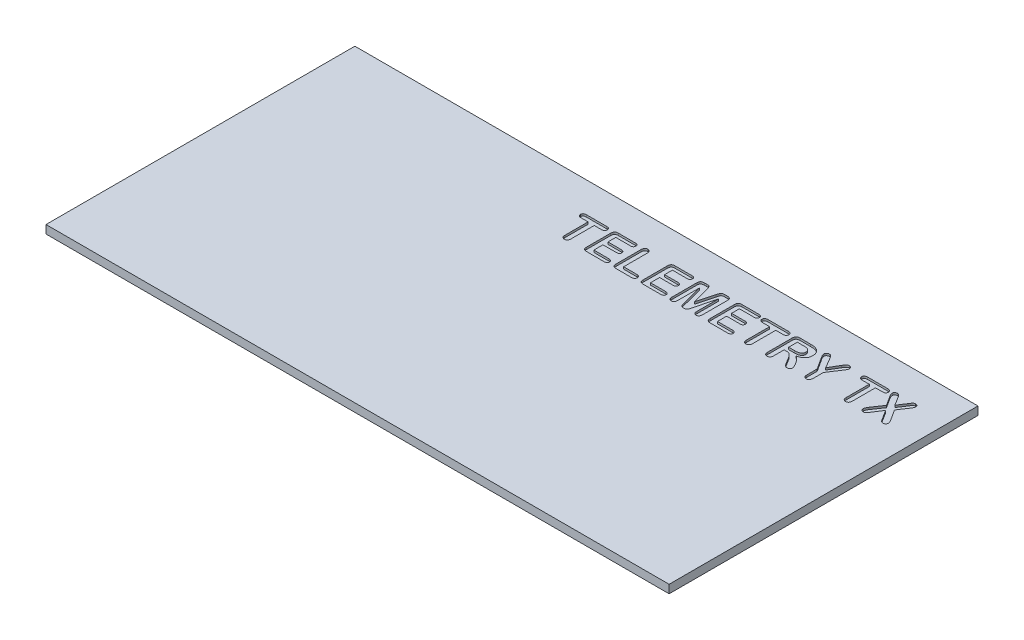
SolidWorks part; units mm, degrees
ref_plane "Front Plane" through (0, 0, 0) normal (0, 0, 1) x (1, 0, 0)
ref_plane "Top Plane" through (0, 0, 0) normal (0, 1, 0) x (1, 0, 0)
ref_plane "Right Plane" through (0, 0, 0) normal (1, 0, 0) x (0, 0, -1)
sketch "Sketch1" plane through (0, 0, 0) normal (0, 1, 0) x (1, 0, 0)
  line L5 (-75.35, 37.35) -> (75.35, 37.35)
  line L6 (-75.35, 37.35) -> (-75.35, -37.35)
  line L7 (-75.35, -37.35) -> (75.35, -37.35)
  line L8 (75.35, 37.35) -> (75.35, -37.35)
  line L9 (-75.35, 37.35) -> (75.35, -37.35) construction
  line L10 (-75.35, -37.35) -> (75.35, 37.35) construction
  point P0 (0, 0)
  dimension "D1" = 150.7
  dimension "D2" = 74.7
extrude "Boss-Extrude1" add sketch "Sketch1" along normal blind 2
sketch "Sketch2" plane through (0, 2, 0) normal (0, 1, 0) x (1, 0, 0)
  line L0 (-75.35, 37.35) -> (-75.35, -37.35) construction
  line L1 (-75.35, 30.35) -> (68.35, 30.35) construction
  line L2 (-75.35, 30.35) -> (-75.35, 22.35) construction
  line L3 (-75.35, 22.35) -> (68.35, 22.35) construction
  line L4 (68.35, 30.35) -> (68.35, 22.35) construction
  line L6 (75.35, -37.35) -> (75.35, 37.35) construction
  line L7 (75.35, 37.35) -> (-75.35, 37.35) construction
  text T0 "TELEMETRY TX" font "Arial Rounded MT Bold" height 8
  point P6 (65.503, 22.3615)
  point P9 (0, 0)
  dimension "D1" = 8
  dimension "D2" = 7
  dimension "D3" = 7
extrude "Cut-Extrude1" cut sketch "Sketch2" against normal blind 0.5
